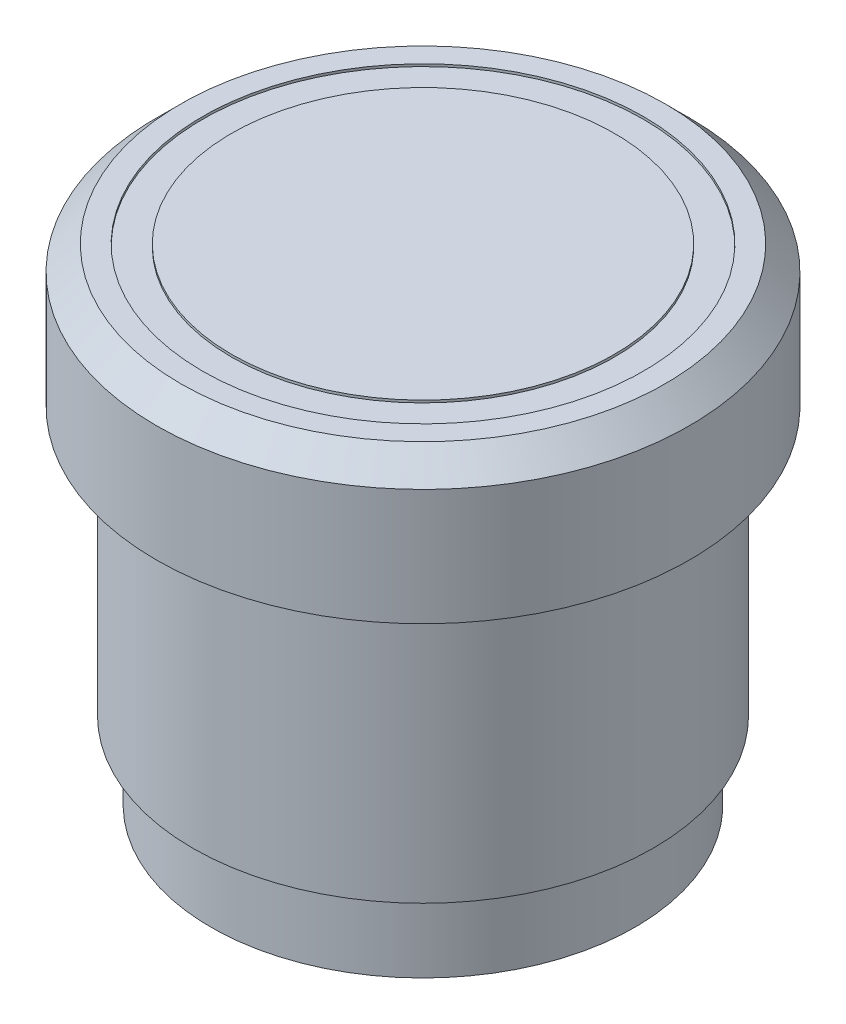
SolidWorks part; units mm, degrees
ref_plane "Front Plane" through (0, 0, 0) normal (0, 0, 1) x (1, 0, 0)
ref_plane "Top Plane" through (0, 0, 0) normal (0, 1, 0) x (1, 0, 0)
ref_plane "Right Plane" through (0, 0, 0) normal (1, 0, 0) x (0, 0, -1)
sketch "Sketch1" plane through (0, 0, 0) normal (1, 0, 0) x (0, 0, -1)
  line L0 (0, 0) -> (0, 50000) construction
  line L1 (0, 20.05) -> (11, 20.05)
  line L2 (11, 20.05) -> (11, 14.25)
  line L3 (11, 14.25) -> (9.5, 14.25)
  line L4 (9.5, 14.25) -> (9.5, 3.2)
  line L5 (9.5, 3.2) -> (8.75, 3.2)
  line L6 (8.75, 3.2) -> (8.75, 0)
  line L7 (8.75, 0) -> (0, 0)
  line L8 (0, 20.05) -> (0, 0)
  dimension "D1" = 20.05
  dimension "D2" = 5.8
  dimension "D3" = 22
  dimension "D4" = 19
  dimension "D5" = 3.2
  dimension "D6" = 17.5
revolve "Revolve1" add sketch "Sketch1" angle 360 about L0
sketch "Sketch2" plane through (0, 20.05, 0) normal (0, 1, 0) x (1, 0, 0)
  circle A0 centre (0, 0) radius 7.9
  circle A1 centre (0, 0) radius 9.1
  dimension "D1" = 15.8
  dimension "D2" = 1.2
extrude "Cut-Extrude1" cut sketch "Sketch2" against normal blind 0.1
chamfer "Chamfer1" distance 1 angle 45 1 edges at (0, 20.05, -11)
